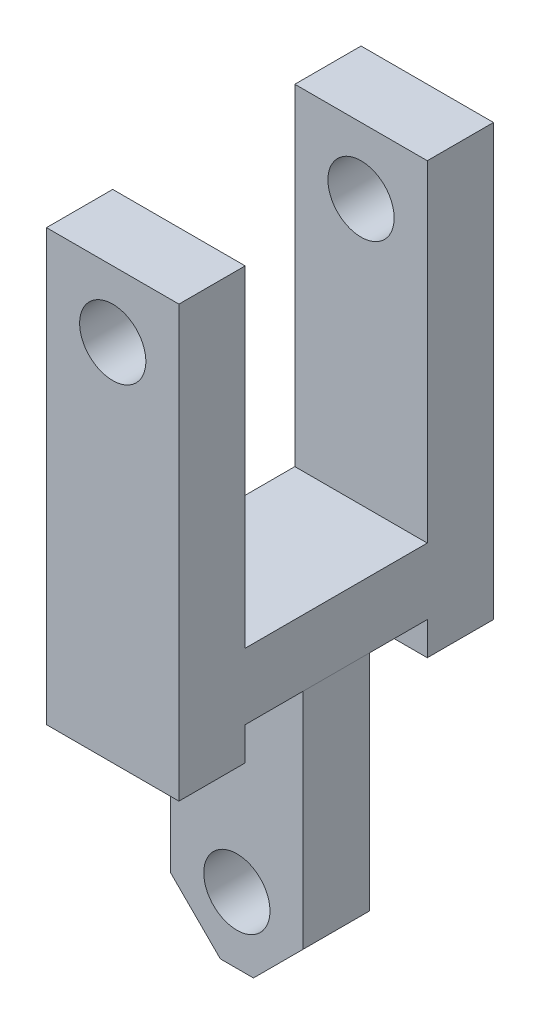
SolidWorks part; units mm, degrees
ref_plane "Front" through (0, 0, 0) normal (0, 0, 1) x (1, 0, 0)
ref_plane "Top" through (0, 0, 0) normal (0, 1, 0) x (1, 0, 0)
ref_plane "Right" through (0, 0, 0) normal (1, 0, 0) x (0, 0, -1)
sketch "Sketch1" plane through (0, 0, 0) normal (0, 0, 1) x (1, 0, 0)
  line L0 (0, 128.5875) -> (0, -128.5875) construction
  line L1 (-25.4, 128.5875) -> (25.4, 128.5875)
  line L2 (-25.4, 128.5875) -> (-25.4, -128.5875)
  line L3 (-25.4, -128.5875) -> (25.4, -128.5875)
  line L4 (25.4, 128.5875) -> (25.4, -128.5875)
  line L5 (-25.4, 0) -> (25.4, 0) construction
  circle A0 centre (0, 103.1875) radius 12.7
  circle A1 centre (0, -103.1875) radius 12.7
  dimension "D4" = 25.4
  dimension "D1" = 50.8
  dimension "D2" = 206.375
  dimension "D3" = 25.4
extrude "Extrude1" add sketch "Sketch1" along normal mid plane 120.65
sketch "Sketch2" plane through (0, 0, 60.325) normal (0, 0, 1) x (1, 0, 0)
  line L2 (-25.4, 128.5875) -> (-25.4, -128.5875) construction
  line L8 (-25.4, -109.5375) -> (-6.35, -128.5875)
  line L9 (-25.4, -128.5875) -> (25.4, -128.5875) construction
  line L10 (-6.35, -128.5875) -> (-25.4, -128.5875)
  line L11 (-25.4, -128.5875) -> (-25.4, -109.5375)
  line L12 (25.4, -109.5375) -> (25.4, -128.5875)
  line L13 (25.4, -128.5875) -> (25.4, 128.5875) construction
  line L14 (25.4, -128.5875) -> (6.35, -128.5875)
  line L15 (6.35, -128.5875) -> (25.4, -109.5375)
  dimension "D1" = 19.05
extrude "Cut-Extrude1" cut sketch "Sketch2" against normal through all
sketch "Sketch3" plane through (0, 0, 0) normal (1, 0, 0) x (0, 0, -1)
  line L1 (-34.925, 128.5875) -> (34.925, 128.5875)
  line L2 (-34.925, 128.5875) -> (-34.925, -36.5125)
  line L3 (-34.925, -36.5125) -> (-60.325, -36.5125)
  line L4 (34.925, 128.5875) -> (34.925, -36.5125)
  line L5 (0, -138.8437) -> (0, 128.5875) construction
  line L6 (-60.325, -109.5375) -> (-60.325, 128.5875) construction
  line L7 (34.925, -36.5125) -> (60.325, -36.5125)
  line L8 (60.325, -109.5375) -> (60.325, 128.5875) construction
  line L9 (60.325, -36.5125) -> (60.325, -128.5875)
  line L10 (60.325, -128.5875) -> (12.7, -128.5875)
  line L11 (60.325, -128.5875) -> (-60.325, -128.5875) construction
  line L12 (12.7, -128.5875) -> (12.7, -23.8125)
  line L13 (12.7, -23.8125) -> (-12.7, -23.8125)
  line L14 (-12.7, -23.8125) -> (-12.7, -128.5875)
  line L15 (-12.7, -128.5875) -> (-60.325, -128.5875)
  line L16 (-60.325, -109.5375) -> (-60.325, -128.5875) construction
  line L17 (-60.325, -128.5875) -> (-60.325, -36.5125)
  line L18 (-60.325, 128.5875) -> (60.325, 128.5875) construction
  dimension "D1" = 69.85
  dimension "D2" = 165.1
  dimension "D3" = 25.4
  dimension "D4" = 152.4
  dimension "D5" = 25.4
  dimension "D6" = 25.4
extrude "Cut-Extrude2" cut sketch "Sketch3" against normal up to next and the other way up to next
sketch "Sketch4" plane through (0, -23.8125, 0) normal (0, -1, 0) x (1, 0, 0)
  line L1 (25.4, 60.325) -> (-25.4, 60.325)
  line L2 (25.4, 60.325) -> (25.4, -60.325)
  line L3 (25.4, -60.325) -> (-25.4, -60.325)
  line L4 (-25.4, 60.325) -> (-25.4, -60.325)
extrude "Extrude2" add sketch "Sketch4" against normal blind 25.4
